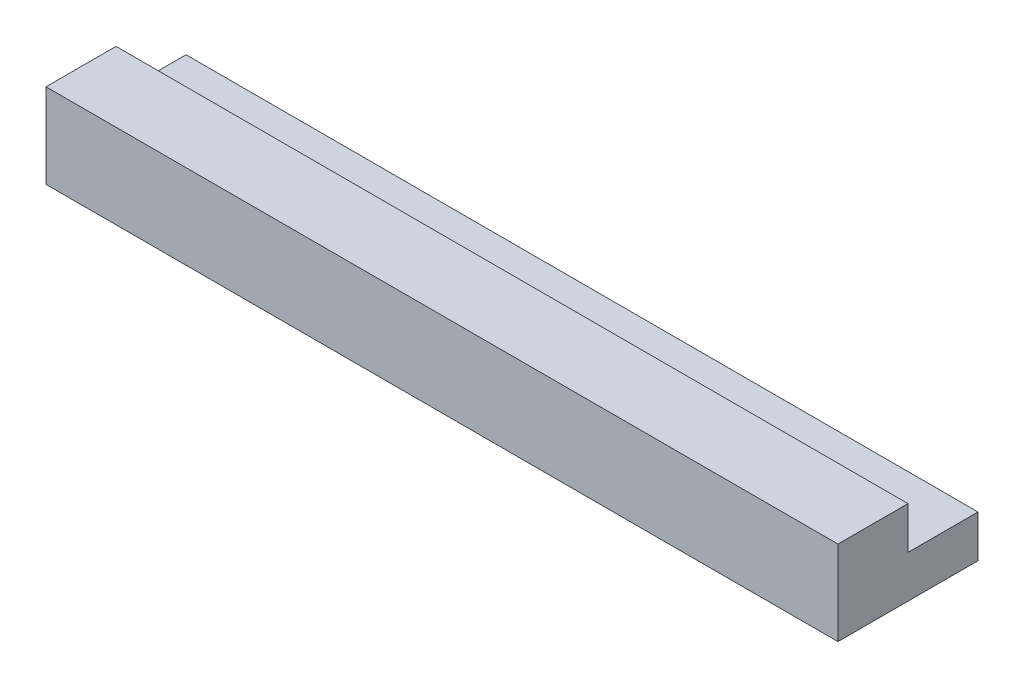
SolidWorks part; units mm, degrees
ref_plane "前视基准面" through (0, 0, 0) normal (0, 0, 1) x (1, 0, 0)
ref_plane "上视基准面" through (0, 0, 0) normal (0, 1, 0) x (1, 0, 0)
ref_plane "右视基准面" through (0, 0, 0) normal (1, 0, 0) x (0, 0, -1)
other "Configuration Table"
sketch "草图1" plane through (0, 0, 0) normal (0, 1, 0) x (1, 0, 0)
  line L1 (-16.4, 2.9) -> (16.4, 2.9)
  line L2 (-16.4, 2.9) -> (-16.4, -2.9)
  line L3 (-16.4, -2.9) -> (16.4, -2.9)
  line L4 (16.4, 2.9) -> (16.4, -2.9)
  line L5 (-16.4, 2.9) -> (16.4, -2.9) construction
  line L6 (-16.4, -2.9) -> (16.4, 2.9) construction
  point P0 (0, 0)
extrude "凸台-拉伸1" add sketch "草图1" along normal blind 1.75
sketch "草图2" plane through (0, 1.75, 0) normal (0, 1, 0) x (1, 0, 0)
  line L1 (-16.4, -2.9) -> (16.4, -2.9)
  line L2 (-16.4, -2.9) -> (-16.4, 0)
  line L3 (-16.4, 0) -> (16.4, 0)
  line L4 (16.4, -2.9) -> (16.4, 0)
  line L6 (16.4, 2.9) -> (-16.4, 2.9) construction
  dimension "D1" = 2.9
extrude "凸台-拉伸2" add sketch "草图2" along normal blind 1.75
